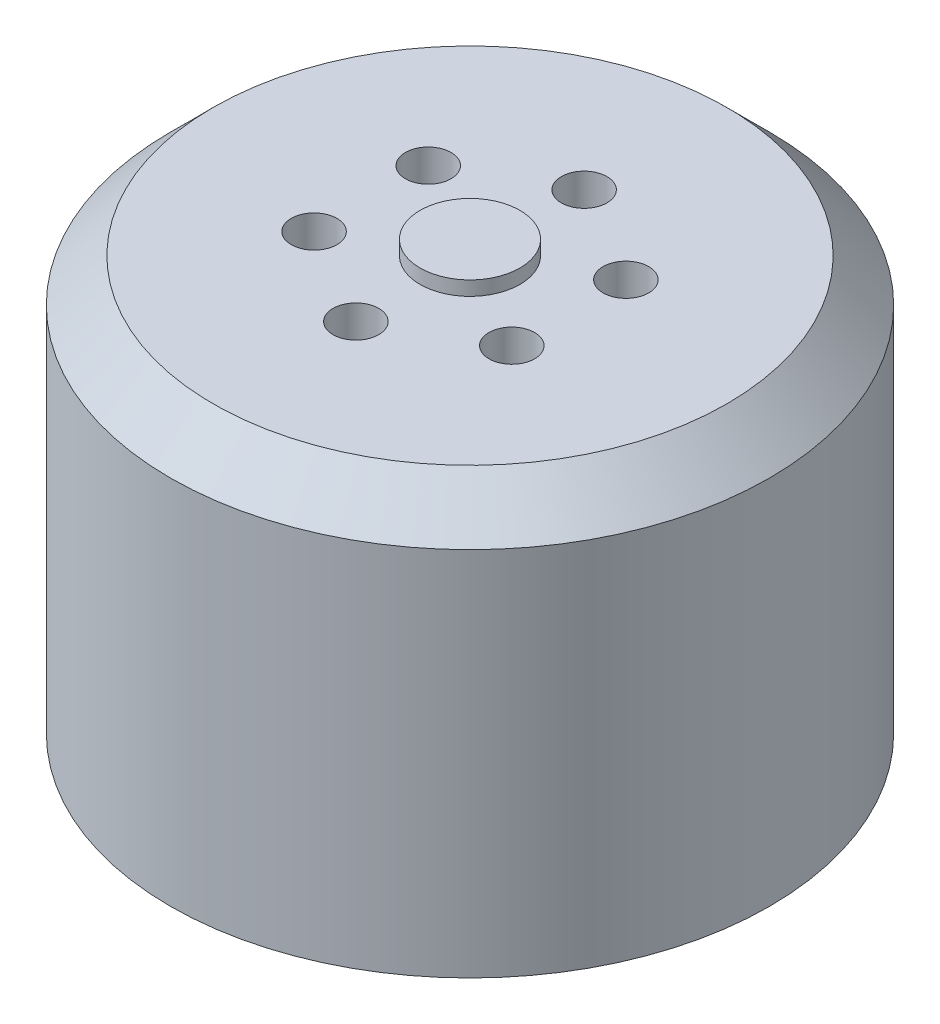
SolidWorks part; units mm, degrees
ref_plane "前视基准面" through (0, 0, 0) normal (0, 0, 1) x (1, 0, 0)
ref_plane "上视基准面" through (0, 0, 0) normal (0, 1, 0) x (1, 0, 0)
ref_plane "右视基准面" through (0, 0, 0) normal (1, 0, 0) x (0, 0, -1)
sketch "草图4" plane through (0, 0, 0) normal (0, 0, 1) x (1, 0, 0)
  line L0 (0, 30.5) -> (-18, 30.5)
  line L1 (-21, 27.5) -> (-21, 1.5)
  line L2 (-21, 1.5) -> (-10, 1.5)
  line L3 (-10, 1.5) -> (-10, 0)
  line L4 (-10, 0) -> (0, 0)
  line L5 (0, 0) -> (0, 30.5)
  line L6 (-18, 30.5) -> (-21, 27.5)
  point P1 (-21, 30.5)
  dimension "D1" = 1.5
  dimension "D2" = 29
  dimension "D3" = 10
  dimension "D4" = 21
revolve "旋转1" add sketch "草图4" angle 360 about L5
sketch "草图5" plane through (0, 30.5, 0) normal (0, 1, 0) x (1, 0, 0)
  circle A0 centre (0, 0) radius 8 construction
  circle A1 centre (0, 8) radius 1.6
  circle A2 centre (6.9282, 4) radius 1.6
  circle A3 centre (6.9282, -4) radius 1.6
  circle A4 centre (0, -8) radius 1.6
  circle A5 centre (-6.9282, -4) radius 1.6
  circle A6 centre (-6.9282, 4) radius 1.6
  point P17 (0, 0)
  dimension "D1" = 3.2
  dimension "D2" = 16
  dimension "D3" = 6
extrude "切除-拉伸1" cut sketch "草图5" against normal blind 5
sketch "草图6" plane through (0, 1.5, 0) normal (0, -1, 0) x (1, 0, 0)
  circle A0 centre (0, 0) radius 18 construction
  circle A1 centre (0, 18) radius 1.6
  circle A2 centre (18, 0) radius 1.6
  circle A3 centre (0, -18) radius 1.6
  circle A4 centre (-18, 0) radius 1.6
  point P14 (0, 0)
  dimension "D1" = 36
  dimension "D2" = 3.2
  dimension "D3" = 4
extrude "切除-拉伸2" cut sketch "草图6" against normal blind 5
sketch "草图7" plane through (0, 30.5, 0) normal (0, 1, 0) x (1, 0, 0)
  circle A0 centre (0, 0) radius 3.5
  dimension "D1" = 7
extrude "凸台-拉伸1" add sketch "草图7" along normal blind 1
